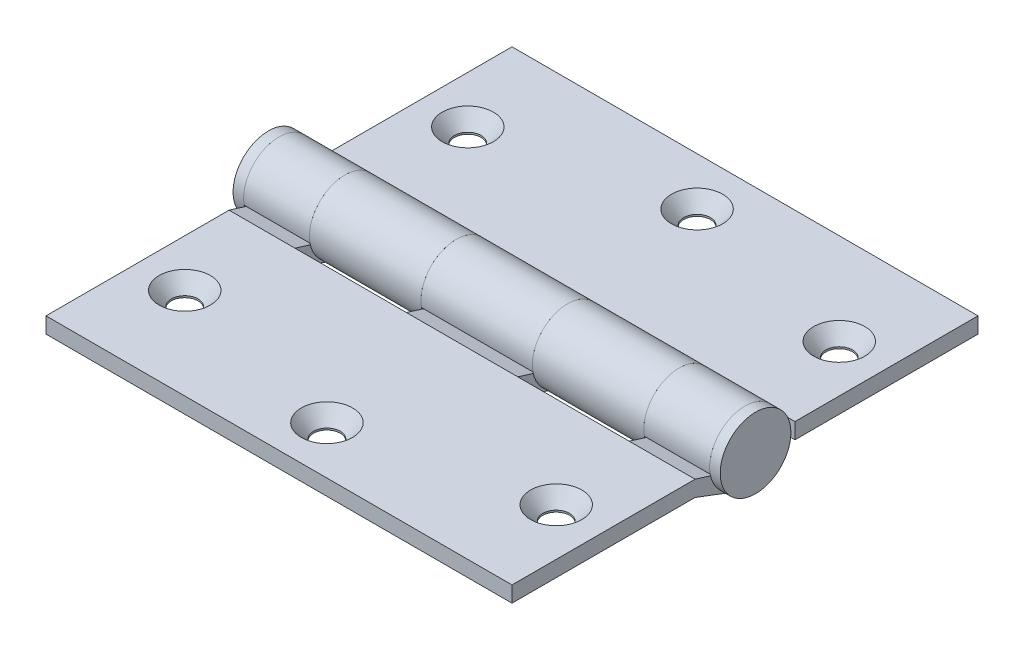
SolidWorks part; units mm, degrees
ref_plane "Front" through (0, 0, 0) normal (0, 0, 1) x (1, 0, 0)
ref_plane "Top" through (0, 0, 0) normal (0, 1, 0) x (1, 0, 0)
ref_plane "Right" through (0, 0, 0) normal (1, 0, 0) x (0, 0, -1)
sketch "Sketch1" plane through (0, 0, 0) normal (1, 0, 0) x (0, 0, -1)
  line L0 (-9.525, -3.6068) -> (-2.3899, -6.3094)
  line L1 (-44.45, -0.5842) -> (-9.525, -0.5842)
  line L2 (-9.525, -0.5842) -> (-0.9971, -3.2227)
  line L3 (-44.45, -3.6068) -> (-9.525, -3.6068)
  line L4 (-44.45, -0.5842) -> (-44.45, -3.6068)
  line L5 (-6.6372, -1.2118) -> (-2.1489, -2.6005)
  arc A0 (-0.9971, -3.2227) -> (-2.1489, -2.6005) centre (0, 0) ccw
  arc A1 (-2.3899, -6.3094) -> (-6.6372, -1.2118) centre (0, 0) ccw
  circle A2 centre (0, 0) radius 6.7469 construction
  circle A3 centre (0, 0) radius 3.3734 construction
  dimension "Pin Dia." = 6.7469
  dimension "Kn Dia" = 13.4937
  dimension "Th" = 3.0226
  dimension "D3" = 0.254
  dimension "Open Width / 2" = 44.45
  dimension "Leaf End" = 34.925
  dimension "Leaf Top" = 0.5842
extrude "Left Leaf" add sketch "Sketch1" along normal mid plane 88.9
sketch "Sketch2" plane through (0, 0, 0) normal (0, 1, 0) x (1, 0, 0)
  line L0 (31.8897, -9.525) -> (31.8897, 6.7469)
  line L2 (0, 6.7469) -> (0, -44.45) construction
  line L3 (44.45, 6.7469) -> (-44.45, 6.7469) construction
  line L4 (31.8897, 6.7469) -> (10.6299, 6.7469)
  line L5 (10.6299, 6.7469) -> (10.6299, -9.525)
  line L7 (44.45, -44.45) -> (-44.45, -44.45) construction
  line L8 (-31.8897, -9.525) -> (-31.8897, 6.7469)
  line L9 (10.6299, -9.525) -> (31.8897, -9.525)
  line L10 (-10.6299, -9.525) -> (-31.8897, -9.525)
  line L11 (-10.6299, 6.7469) -> (-10.6299, -9.525)
  line L12 (-31.8897, 6.7469) -> (-10.6299, 6.7469)
  line L14 (-10.6299, 6.7469) -> (10.6299, 6.7469) construction
  dimension "Knuckle Lg" = 21.2598
extrude "Cut-Extrude1" cut sketch "Sketch2" against normal through all and the other way through all
sketch "Sketch3" plane through (31.8897, 0, 0) normal (1, 0, 0) x (0, 0, -1)
  line L0 (0, 6.7469) -> (0, -3.6068) construction
  line L1 (-44.45, -3.6068) -> (-9.525, -3.6068) construction
  line L2 (9.525, -3.6068) -> (2.3899, -6.3094)
  line L3 (9.525, -0.5842) -> (0.9971, -3.2227)
  line L4 (2.1489, -2.6005) -> (6.6372, -1.2118)
  line L6 (9.525, -3.6068) -> (44.45, -3.6068)
  line L7 (44.45, -3.6068) -> (44.45, -0.5842)
  line L9 (-44.45, -0.5842) -> (-44.45, -3.6068) construction
  line L10 (44.45, -0.5842) -> (9.525, -0.5842)
  arc A0 (-2.3899, -6.3094) -> (-6.6372, -1.2118) centre (0, 0) ccw construction
  circle A5 centre (0, 0) radius 6.7469 construction
  arc A6 (2.3899, -6.3094) -> (6.6372, -1.2118) centre (0, 0) cw
  arc A7 (-0.9971, -3.2227) -> (-2.1489, -2.6005) centre (0, 0) ccw construction
  arc A8 (2.1489, -2.6005) -> (0.9971, -3.2227) centre (0, 0) ccw
extrude "Right Leaf" add sketch "Sketch3" against normal up to surface (21.2598 mm away) separate body up to face at (10.6299, -0.5961, 3.0583)
mirror "Mirror1" about plane through (0, 0, 0) normal (1, 0, 0) of bodies 110
sketch "Sketch4" plane through (0, 0, 0) normal (-1, 0, 0) x (0, 0, 1)
  line L0 (-9.525, -0.5842) -> (-9.525, -3.6068)
  line L1 (-44.45, -0.5842) -> (-9.525, -0.5842)
  line L2 (0, 6.7469) -> (0, -3.6068) construction
  line L6 (-9.525, -3.6068) -> (-44.45, -3.6068)
  line L8 (-44.45, -3.6068) -> (-44.45, -0.5842)
extrude "Extrude3" add sketch "Sketch4" along normal up to surface and the other way up to surface
combine bodies "Combine1" operation type add bodies to combine 125 110 111
sketch "Sketch6" plane through (0, 0, 0) normal (0, 1, 0) x (1, 0, 0)
  line L0 (24.5662, 0) -> (-23.3403, 0) construction
  line L1 (44.45, -6.7469) -> (44.45, 6.7469) construction
  line L2 (-44.45, 0) -> (44.45, 0)
  line L3 (-44.45, 0) -> (-44.45, -3.3734)
  line L4 (-44.45, -3.3734) -> (44.45, -3.3734)
  line L5 (44.45, 0) -> (44.45, -3.3734)
  line L6 (-44.45, -3.3734) -> (-44.45, 3.3734) construction
  dimension "D1" = 6.7469
revolve "Pin" add sketch "Sketch6" angle 360 about L0
sketch "Sketch7" plane through (0, 0, 0) normal (0, 1, 0) x (1, 0, 0)
  line L0 (24.5662, 0) -> (-23.3403, 0) construction
  line L1 (0, 44.45) -> (0, -44.45) construction
  line L2 (24.5662, 0) -> (-23.3403, 0) construction
  line L3 (-46.4651, 0) -> (-46.4651, -6.7469)
  line L4 (-46.4651, 0) -> (-44.45, 0)
  line L5 (-44.45, 0) -> (-44.45, -6.7469)
  line L6 (-44.45, 44.45) -> (44.45, 44.45) construction
  line L7 (-46.4651, -6.7469) -> (-44.45, -6.7469)
  line L8 (46.4651, 0) -> (46.4651, -6.7469)
  line L9 (44.45, 0) -> (44.45, -6.7469)
  line L10 (46.4651, 0) -> (44.45, 0)
  line L11 (46.4651, -6.7469) -> (44.45, -6.7469)
  dimension "D1" = 2.0151
revolve "Spun Pin" add sketch "Sketch7" angle 360 about L0
sketch "Sketch8" plane through (0, -0.5842, 0) normal (0, 1, 0) x (-1, 0, 0)
  line L3 (44.45, 0) -> (-44.45, 0) construction
  line L4 (0, -44.45) -> (0, 44.45) construction
  line L5 (44.45, -44.45) -> (-44.45, -44.45) construction
  line L6 (0, 44.45) -> (0, 9.525) construction
  line L7 (-44.45, 44.45) -> (44.45, 44.45) construction
  point P3 (35.433, -27.0002)
  point P4 (-35.433, -27.0002)
  point P8 (-35.433, 27.0002)
  point P9 (35.433, 27.0002)
  point P26 (0, -35.306)
  point P27 (0, 35.306)
  dimension "Hole Dist" = 35.433
  dimension "Hole Dist2" = 17.4498
  dimension "Hole Dist3" = 9.144
hole_wizard "CSK for #10 Flat Head Machine Screw1" positions "3DSketch1" profile "Sketch9" countersink size "#10" standard "Ansi Inch" end condition through all
sketch3d "3DSketch1"
  point P30 (-35.433, -0.5842, 27.0002)
  point P33 (-35.433, -0.5842, -27.0002)
  point P36 (35.433, -0.5842, -27.0002)
  point P39 (35.433, -0.5842, 27.0002)
  point P56 (0, -0.5842, -35.306)
  point P59 (0, -0.5842, 35.306)
sketch "Sketch9" plane through (-35.433, -0.5842, 27.0002) normal (1, 0, 0) x (0, 0, 1)
  line L0 (0, 0) -> (0, 6.1627)
  line L1 (0, 6.1627) -> (2.5527, 6.1627)
  line L2 (2.5527, 6.1627) -> (2.5527, 2.6882)
  line L3 (2.5527, 2.6882) -> (4.8895, 0)
  line L5 (4.8895, 0) -> (0, 0)
  line L6 (-2.5527, 2.6882) -> (-4.8895, 0) construction
  line L11 (0, -6.35) -> (0, 107.95) construction
  dimension "Thru Hole Dia." = 5.1054
  dimension "Thru Hole Depth" = 6.1627
  dimension "Near C'Sink Dia." = 9.779
  dimension "Near C'Sink Angle" = 82
equation "\"D1@Sketch7\"=\"Th@Sketch1\"/1.5"
equation "\"D1@Sketch6\" = \"Pin Dia.@Sketch1\""
